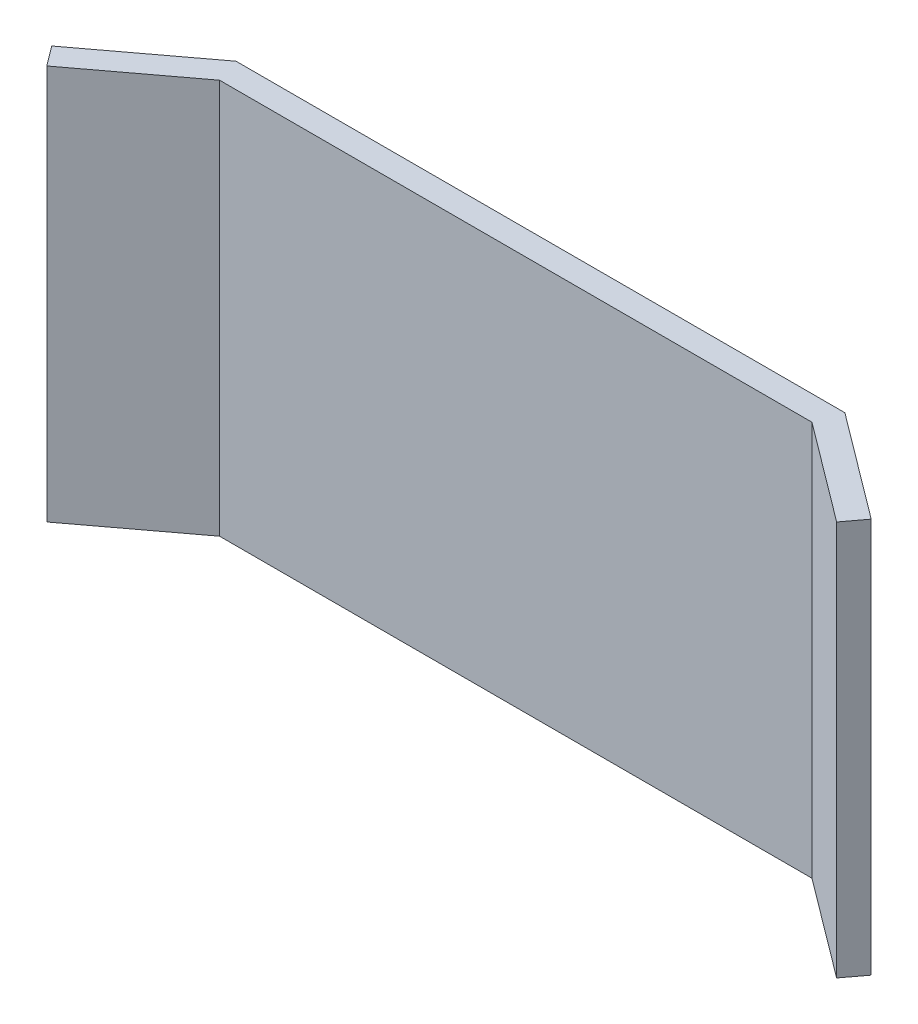
SolidWorks part; units mm, degrees
ref_plane "Front Plane" through (0, 0, 0) normal (0, 0, 1) x (1, 0, 0)
ref_plane "Top Plane" through (0, 0, 0) normal (0, 1, 0) x (1, 0, 0)
ref_plane "Right Plane" through (0, 0, 0) normal (1, 0, 0) x (0, 0, -1)
sketch "Sketch1" plane through (0, 0, 0) normal (0, 1, 0) x (1, 0, 0)
  line L0 (-60, 0) -> (60, 0)
  line L1 (60, 0) -> (80, -15)
  line L2 (0, 11.4148) -> (0, -13.0209) construction
  line L3 (-60, 0) -> (-80, -15)
  line L4 (61.6667, 5) -> (83, -11)
  line L5 (-61.6667, 5) -> (61.6667, 5)
  line L6 (-61.6667, 5) -> (-83, -11)
  line L7 (-83, -11) -> (-80, -15)
  line L8 (83, -11) -> (80, -15)
  point P4 (0, 0)
  dimension "D1" = 60
  dimension "D2" = 15
  dimension "D3" = 20
  dimension "D4" = 5
extrude "Boss-Extrude1" add sketch "Sketch1" against normal blind 80
sketch "Sketch2" plane through (0, 0, -5) normal (0, 0, -1) x (-1, 0, 0)
  line L0 (-61.6667, -80) -> (61.6667, -80) construction
  line L1 (-40, -55) -> (40, -55)
  line L2 (-40, -55) -> (-40, -65)
  line L3 (-40, -65) -> (40, -65)
  line L4 (40, -55) -> (40, -65)
  dimension "D1" = 10
  dimension "D2" = 80
  dimension "D3" = 40
  dimension "D4" = 15
extrude "Boss-Extrude2" add sketch "Sketch2" along normal blind 25
